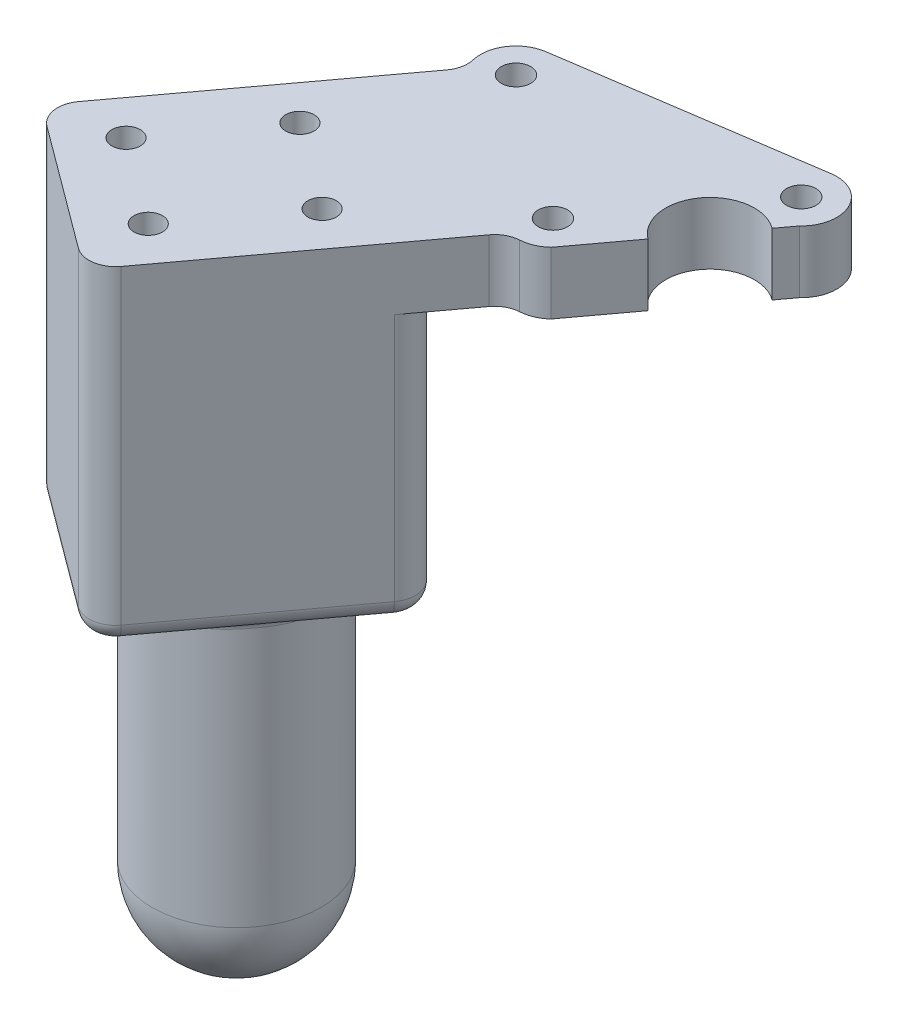
SolidWorks part; units mm, degrees
ref_plane "Front Plane" through (0, 0, 0) normal (0, 0, 1) x (1, 0, 0)
ref_plane "Top Plane" through (0, 0, 0) normal (0, 1, 0) x (1, 0, 0)
ref_plane "Right Plane" through (0, 0, 0) normal (1, 0, 0) x (0, 0, -1)
sketch "Sketch1" plane through (0, 0, 0) normal (0, 1, 0) x (1, 0, 0)
  line L0 (1.4975, 0.7868) -> (-36.9339, 98.5008) construction
  line L6 (-56.6569, 90.4835) -> (-36.9937, 86.8285) construction
  line L17 (-34.7298, 79.5308) -> (-58.048, 63.5226) construction
  line L18 (-61.6543, 88.9381) -> (-90.7933, 94.3545) construction
  line L19 (1.4975, 0.7868) -> (79.9099, 31.6269) construction
  line L20 (-94.291, 91.9533) -> (-97.3978, 75.2396) construction
  line L21 (-65.8576, 66.3255) -> (-94.9966, 71.7418) construction
  line L22 (6.159, 94.65) -> (23.8009, 118.4656) construction
  line L23 (9.5157, 132.7811) -> (23.176, 122.6619) construction
  line L24 (-12.3225, 108.3406) -> (5.3194, 132.1562) construction
  line L25 (-25.6246, 83.1119) -> (2.3512, 87.278) construction
  line L26 (-17.0338, 106.0675) -> (-28.9387, 89.9966) construction
  line L27 (59.6519, -88.9099) -> (39.9887, -85.2549) construction
  line L28 (37.7248, -77.9572) -> (61.043, -61.949) construction
  line L29 (64.6494, -87.3645) -> (93.7884, -92.7809) construction
  line L30 (97.2861, -90.3797) -> (100.3929, -73.666) construction
  line L31 (68.8527, -64.7518) -> (97.9916, -70.1682) construction
  line L32 (-3.1639, -93.0764) -> (-20.8058, -116.8919)
  line L33 (-6.5207, -131.2074) -> (-20.1809, -121.0883)
  line L34 (15.3176, -106.767) -> (-2.3243, -130.5825)
  line L35 (28.6196, -81.5383) -> (0.6438, -85.7043)
  line L36 (20.0288, -104.4939) -> (31.9337, -88.423)
  circle A33 centre (-56.6569, 86.4835) radius 1.65 construction
  circle A34 centre (-36.9937, 82.8285) radius 1.65 construction
  circle A35 centre (-40.6487, 63.1653) radius 1.65 construction
  circle A36 centre (-60.3119, 66.8203) radius 1.65 construction
  arc A37 (-56.6569, 90.4835) -> (-59.1993, 89.5716) centre (-56.6569, 86.4835) ccw construction
  arc A38 (-34.7298, 79.5308) -> (-36.9937, 86.8285) centre (-36.9937, 82.8285) ccw construction
  arc A39 (-63.7941, 64.8521) -> (-58.048, 63.5226) centre (-60.3119, 66.8203) ccw construction
  arc A40 (-65.8576, 66.3255) -> (-63.7941, 64.8521) centre (-66.4058, 63.376) cw construction
  arc A41 (-59.1993, 89.5716) -> (-61.6543, 88.9381) centre (-61.1061, 91.8876) cw construction
  arc A42 (-90.7933, 94.3545) -> (-94.291, 91.9533) centre (-91.3416, 91.405) ccw construction
  arc A43 (-94.9966, 71.7418) -> (-97.3978, 75.2396) centre (-94.4483, 74.6913) cw construction
  arc A44 (23.8009, 118.4656) -> (23.176, 122.6619) centre (21.3903, 120.2513) ccw construction
  arc A45 (5.3194, 132.1562) -> (9.5157, 132.7811) centre (7.73, 130.3704) cw construction
  arc A46 (-14.5513, 107.1319) -> (-12.3225, 108.3406) centre (-14.7332, 110.1263) ccw construction
  arc A47 (6.159, 94.65) -> (5.6521, 92.1657) centre (8.5696, 92.8643) ccw construction
  arc A48 (5.6521, 92.1657) -> (2.3512, 87.278) centre (1.7621, 91.2343) cw construction
  arc A49 (-25.6246, 83.1119) -> (-28.9387, 89.9966) centre (-26.2137, 87.0683) cw construction
  arc A50 (-17.0338, 106.0675) -> (-14.5513, 107.1319) centre (-14.3088, 103.1392) cw construction
  circle A51 centre (1.7621, 91.2343) radius 1.65 construction
  circle A52 centre (-10.1428, 75.1634) radius 1.65 construction
  circle A53 centre (-26.2137, 87.0683) radius 1.65 construction
  circle A54 centre (-14.3088, 103.1392) radius 1.65 construction
  circle A55 centre (59.6519, -84.9099) radius 1.65 construction
  circle A56 centre (39.9887, -81.2549) radius 1.65 construction
  circle A57 centre (43.6437, -61.5917) radius 1.65 construction
  circle A58 centre (63.3069, -65.2467) radius 1.65 construction
  arc A59 (59.6519, -88.9099) -> (62.1943, -87.9979) centre (59.6519, -84.9099) ccw construction
  arc A60 (37.7248, -77.9572) -> (39.9887, -85.2549) centre (39.9887, -81.2549) ccw construction
  arc A61 (66.7892, -63.2785) -> (61.043, -61.949) centre (63.3069, -65.2467) ccw construction
  arc A62 (68.8527, -64.7518) -> (66.7892, -63.2785) centre (69.4009, -61.8024) cw construction
  arc A63 (62.1943, -87.9979) -> (64.6494, -87.3645) centre (64.1012, -90.314) cw construction
  arc A64 (93.7884, -92.7809) -> (97.2861, -90.3797) centre (94.3366, -89.8314) ccw construction
  arc A65 (97.9916, -70.1682) -> (100.3929, -73.666) centre (97.4434, -73.1177) cw construction
  arc A66 (-20.8058, -116.8919) -> (-20.1809, -121.0883) centre (-18.3952, -118.6777) ccw
  arc A67 (-2.3243, -130.5825) -> (-6.5207, -131.2074) centre (-4.7349, -128.7968) cw
  arc A68 (17.5464, -105.5582) -> (15.3176, -106.767) centre (17.7282, -108.5527) ccw
  arc A69 (-3.1639, -93.0764) -> (-2.657, -90.5921) centre (-5.5746, -91.2907) ccw
  arc A70 (-2.657, -90.5921) -> (0.6438, -85.7043) centre (1.233, -89.6607) cw
  arc A71 (28.6196, -81.5383) -> (31.9337, -88.423) centre (29.2088, -85.4947) cw
  arc A72 (20.0288, -104.4939) -> (17.5464, -105.5582) centre (17.3039, -101.5656) cw
  circle A73 centre (1.233, -89.6607) radius 1.65
  circle A74 centre (13.1379, -73.5898) radius 1.65 construction
  circle A75 centre (29.2088, -85.4947) radius 1.65
  circle A76 centre (17.3039, -101.5656) radius 1.65
  dimension "D1" = 8
  dimension "D2" = 8
  dimension "D3" = 8
  dimension "D4" = 3
  dimension "D5" = 3
extrude "Boss-Extrude1" add sketch "Sketch1" along normal mid plane 7
sketch "Sketch8" plane through (0, 3.5, 0) normal (0, 1, 0) x (1, 0, 0)
  line L0 (20.0288, -104.4939) -> (31.9337, -88.423) construction
  circle A0 centre (27.648, -94.2085) radius 5
  point P4 (0, 0)
  dimension "D2" = 10
  dimension "D1" = 7.2
extrude "Cut-Extrude3" cut sketch "Sketch8" against normal blind 10
sketch "Sketch9" plane through (0, 3.5, 0) normal (0, 1, 0) x (1, 0, 0)
  line L0 (-14.6006, -117.7551) -> (-4.9581, -124.8981) construction
  line L1 (-6.5207, -131.2074) -> (-20.1809, -121.0883) construction
  line L2 (-6.2672, -106.5055) -> (3.3753, -113.6484) construction
  line L3 (15.3176, -106.767) -> (-2.3243, -130.5825) construction
  circle A0 centre (-6.2672, -106.5055) radius 1.6
  circle A1 centre (3.3753, -113.6484) radius 1.6
  circle A2 centre (-4.9581, -124.8981) radius 1.6
  circle A3 centre (-14.6006, -117.7551) radius 1.6
  dimension "D7" = 3.2
  dimension "D1" = 14
  dimension "D2" = 6
  dimension "D3" = 5.5
  dimension "D4" = 5.5
  dimension "D5" = 12
  dimension "D6" = 12
extrude "Cut-Extrude4" cut sketch "Sketch9" against normal blind 10
sketch "Sketch11" plane through (0, -3.5, 0) normal (0, -1, 0) x (1, 0, 0)
  line L0 (-13.3508, 126.1479) -> (3.316, 103.6486) construction
  line L1 (-6.5207, 131.2074) -> (-20.1809, 121.0883) construction
  line L2 (-3.5141, 98.589) -> (10.1462, 108.7082)
  line L3 (-3.1639, 93.0764) -> (-20.8058, 116.8919) construction
  line L5 (15.3176, 106.767) -> (-2.3243, 130.5825) construction
  line L15 (-20.8058, 116.8919) -> (-3.1639, 93.0764)
  line L16 (0.6438, 85.7043) -> (28.6196, 81.5383)
  line L17 (31.9337, 88.423) -> (20.0288, 104.4939)
  line L18 (15.3176, 106.767) -> (-2.3243, 130.5825)
  line L19 (-6.5207, 131.2074) -> (-20.1809, 121.0883)
  line L20 (-20.8058, 116.8919) -> (-7.7105, 99.2139)
  line L23 (10.7711, 112.9045) -> (-2.3243, 130.5825)
  line L24 (-6.5207, 131.2074) -> (-20.1809, 121.0883)
  arc A7 (-3.5141, 98.589) -> (-7.7105, 99.2139) centre (-5.2998, 100.9997) cw
  arc A8 (10.1462, 108.7082) -> (10.7711, 112.9045) centre (8.3604, 111.1188) ccw
  arc A14 (-2.657, 90.5921) -> (-3.1639, 93.0764) centre (-5.5746, 91.2907) ccw
  arc A15 (-2.657, 90.5921) -> (0.6438, 85.7043) centre (1.233, 89.6607) ccw
  arc A16 (28.6196, 81.5383) -> (31.9337, 88.423) centre (29.2088, 85.4947) ccw
  arc A17 (20.0288, 104.4939) -> (17.5464, 105.5582) centre (17.3039, 101.5656) ccw
  arc A18 (15.3176, 106.767) -> (17.5464, 105.5582) centre (17.7282, 108.5527) ccw
  arc A19 (-2.3243, 130.5825) -> (-6.5207, 131.2074) centre (-4.7349, 128.7968) ccw
  arc A20 (-20.1809, 121.0883) -> (-20.8058, 116.8919) centre (-18.3952, 118.6777) ccw
  arc A26 (-2.3243, 130.5825) -> (-6.5207, 131.2074) centre (-4.7349, 128.7968) ccw
  arc A27 (-20.1809, 121.0883) -> (-20.8058, 116.8919) centre (-18.3952, 118.6777) ccw
  point P15 (-5.9247, 96.8033)
  point P20 (12.5568, 110.4939)
  dimension "D3" = 3
  dimension "D1" = 28
  dimension "D2" = 0
extrude "Boss-Extrude5" add sketch "Sketch11" along normal blind 30
fillet "Fillet4" radius 2 8 edges at (-5.7417, -33.5, 98.0324) (3.316, -33.5, 103.6486) (11.3277, -33.5, 110.6769) (4.2234, -33.5, 121.7435) (-4.2931, -33.5, 131.7641) (-14.2582, -33.5, 108.0529) (-21.3625, -33.5, 119.1195) (-13.3508, -33.5, 126.1479)
sketch "Sketch13" plane through (0, -33.5, 0) normal (0, -1, 0) x (1, 0, 0)
  line L0 (-12.1603, 124.5408) -> (2.1255, 105.2557) construction
  line L1 (-5.3302, 129.6004) -> (-18.9904, 119.4812) construction
  line L2 (-4.7046, 100.1961) -> (8.9557, 110.3153) construction
  line L4 (9.164, 111.7141) -> (-3.9314, 129.3921) construction
  line L5 (2.6163, 120.5531) -> (-12.6511, 109.2434) construction
  line L6 (-19.1987, 118.0824) -> (-6.1034, 100.4044) construction
  circle A0 centre (-5.0174, 114.8982) radius 9.5
extrude "Boss-Extrude6" add sketch "Sketch13" along normal blind 30
fillet "Fillet5" radius 1 2 edges at (-10.6722, -33.5, 122.5319) (0.6374, -33.5, 107.2646)
sketch "Sketch14" plane through (0, -63.5, 0) normal (0, -1, 0) x (1, 0, 0)
  line L0 (-5.0174, 124.3982) -> (-5.0174, 105.3982) construction
  line L1 (-5.0174, 124.3982) -> (-5.0174, 105.3982)
  circle A0 centre (-5.0174, 114.8982) radius 9.5 construction
  arc A1 (-0.5192, 123.2658) -> (-14.3325, 113.0333) centre (-5.0174, 114.8982) ccw construction
  arc A2 (-5.0174, 105.3982) -> (-5.0174, 124.3982) centre (-5.0174, 114.8982) ccw
revolve "Revolve2" add sketch "Sketch14" angle 180 about L0
